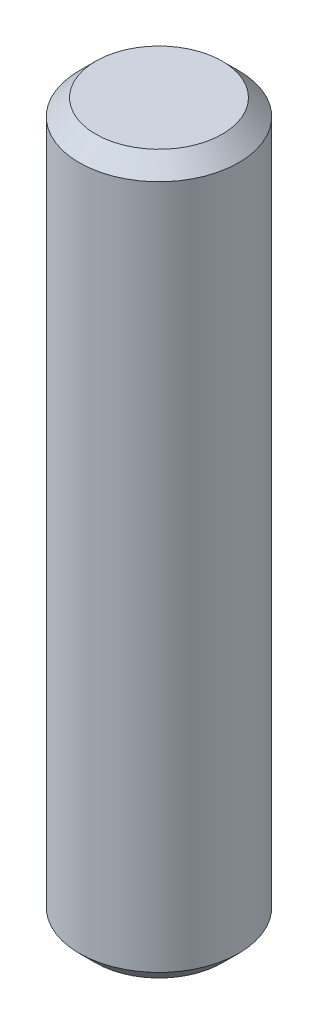
SolidWorks part; units mm, degrees
material "Cast Carbon Steel"
ref_plane "Front Plane" through (0, 0, 0) normal (0, 0, 1) x (1, 0, 0)
ref_plane "Top Plane" through (0, 0, 0) normal (0, 1, 0) x (1, 0, 0)
ref_plane "Right Plane" through (0, 0, 0) normal (1, 0, 0) x (0, 0, -1)
sketch "Sketch1" plane through (0, 0, 0) normal (0, 1, 0) x (1, 0, 0)
  circle A0 centre (0, 0) radius 2
  dimension "D1" = 4
extrude "Boss-Extrude1" add sketch "Sketch1" along normal blind 18
chamfer "Chamfer1" distance 0.413 angle 45 2 edges at (0, 0, 2) (0, 18, 2)
